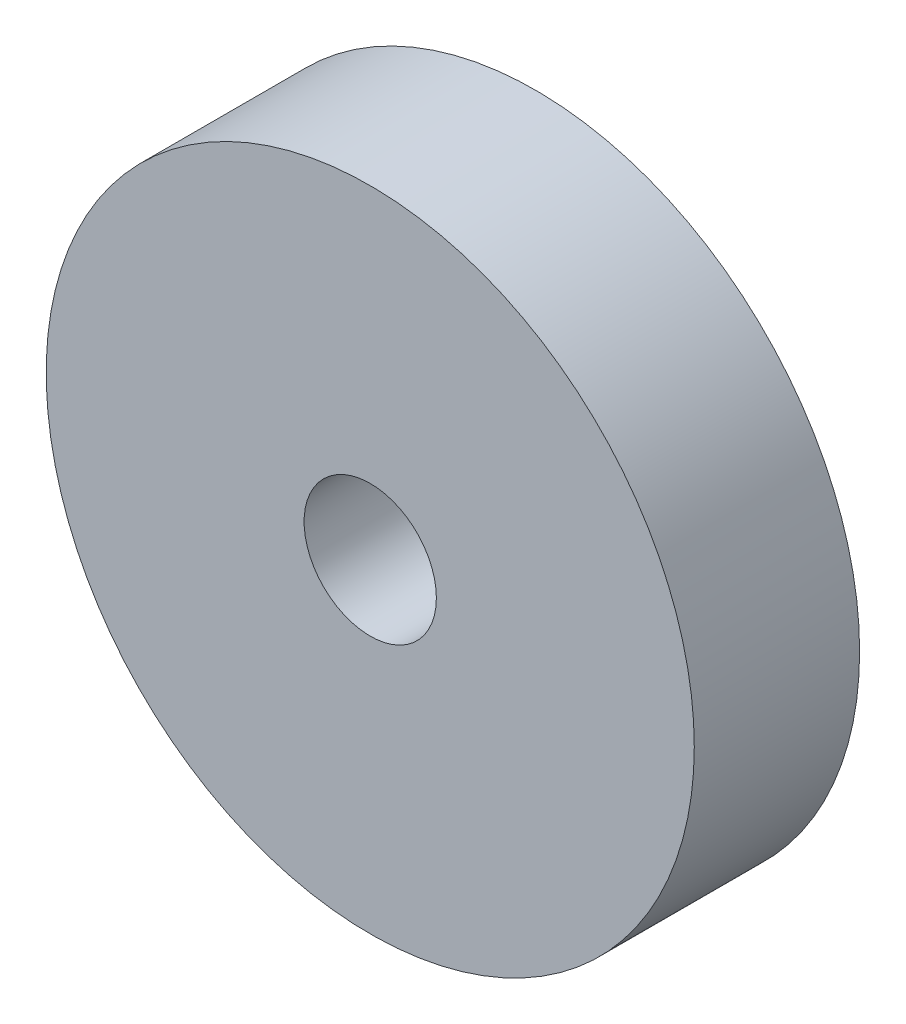
SolidWorks part; units mm, degrees
material "HYPALON"
ref_plane "Front Plane" through (0, 0, 0) normal (0, 0, 1) x (1, 0, 0)
ref_plane "Top Plane" through (0, 0, 0) normal (0, 1, 0) x (1, 0, 0)
ref_plane "Right Plane" through (0, 0, 0) normal (1, 0, 0) x (0, 0, -1)
sketch "Sketch1" plane through (0, 0, 0) normal (0, 0, 1) x (1, 0, 0)
  circle A0 centre (0, 0) radius 98
  circle A1 centre (0, 0) radius 20
  dimension "D1" = 196
  dimension "D2" = 40
extrude "Boss-Extrude1" add sketch "Sketch1" along normal blind 50
